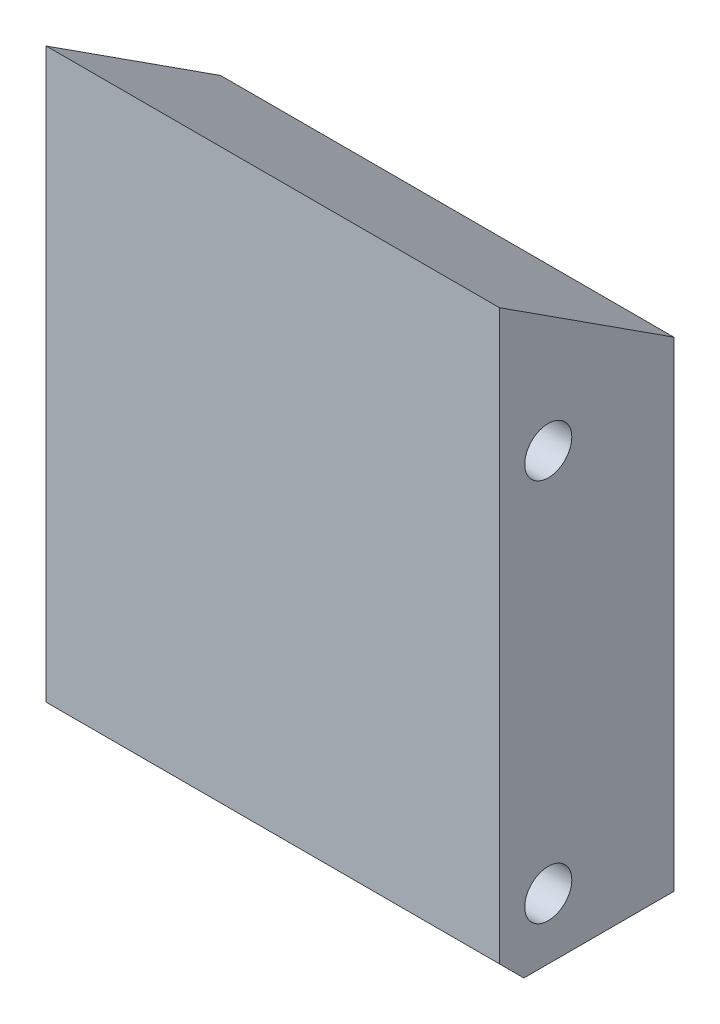
SolidWorks part; units mm, degrees
ref_plane "Plano frontal" through (0, 0, 0) normal (0, 0, 1) x (1, 0, 0)
ref_plane "Plano superior" through (0, 0, 0) normal (0, 1, 0) x (1, 0, 0)
ref_plane "Plano direito" through (0, 0, 0) normal (1, 0, 0) x (0, 0, -1)
sketch "Esboço1" plane through (0, 0, 0) normal (0, 0, 1) x (1, 0, 0)
  line L1 (-13, -17) -> (13, -17)
  line L2 (-13, -17) -> (-13, 17)
  line L3 (-13, 17) -> (13, 17)
  line L4 (13, -17) -> (13, 17)
  line L5 (-13, -17) -> (13, 17) construction
  line L6 (-13, 17) -> (13, -17) construction
  point P0 (0, 0)
extrude "Ressalto-extrusão1" add sketch "Esboço1" along normal blind 10
chamfer "Chanfro1" distance 1.4 angle 45 1 edges at (0, -17, 10)
sketch "Esboço2" plane through (0, 0, 0) normal (1, 0, 0) x (0, 0, -1)
  line L0 (-10, 17) -> (0, 17)
  line L1 (0, 17) -> (0, 10.5381)
  line L2 (0, 17) -> (0, -17) construction
  line L3 (0, 10.5381) -> (-10, 17)
  point P4 (0, 11.1756)
extrude "Corte-extrusão1" cut sketch "Esboço2" against normal through all both and the other way through all
ref_plane "Plano1" through (-13, 0, 0) normal (-1, 0, 0) x (0, 0, 1)
sketch "Esboço3" plane through (-13, 0, 0) normal (-1, 0, 0) x (0, 0, 1)
  line L1 (10, 17) -> (10, -15.6) construction
  circle A0 centre (7.2, 8.5) radius 1.025
  circle A1 centre (7.2, -13.5) radius 1.025
  point P7 (0, 0)
  dimension "D1" = 2.8
  dimension "D3" = 22
  dimension "D2" = 8.5
extrude "Corte-extrusão2" cut sketch "Esboço3" against normal blind 10
ref_plane "Plano2" through (13, 0, 0) normal (1, 0, 0) x (0, 0, -1)
sketch "Esboço4" plane through (13, 0, 0) normal (1, 0, 0) x (0, 0, -1)
  line L1 (-10, -15.6) -> (-10, 17) construction
  circle A0 centre (-7.2, 8.5) radius 1.35
  circle A1 centre (-7.2, -13.5) radius 1.35
  point P7 (0, 0)
  dimension "D1" = 8.5
  dimension "D2" = 2.8
  dimension "D3" = 22
extrude "Corte-extrusão3" cut sketch "Esboço4" against normal blind 10
ref_plane "Plano3" through (0, 0, 0) normal (0, 0, -1) x (-1, 0, 0)
sketch "Esboço5" plane through (0, 0, 0) normal (0, 0, -1) x (-1, 0, 0)
  circle A0 centre (7, 0) radius 1.35
  circle A1 centre (0, -7) radius 1.35
  circle A2 centre (-7, 0) radius 1.35
  circle A3 centre (0, 7) radius 1.35
  dimension "D1" = 7
  dimension "D2" = 4
extrude "Corte-extrusão4" cut sketch "Esboço5" against normal blind 4
